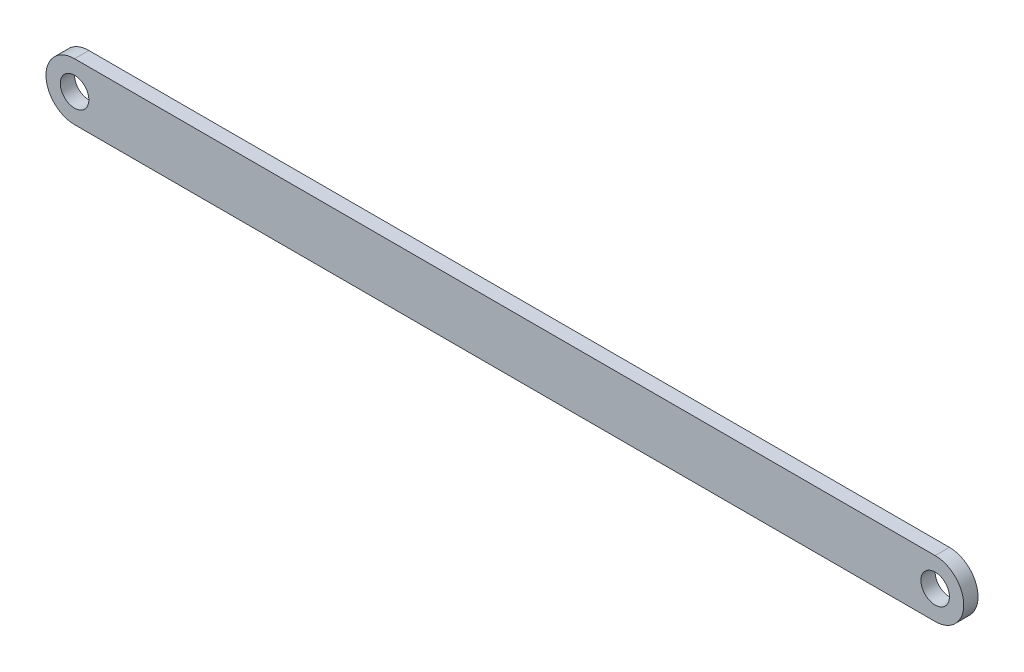
SolidWorks part; units mm, degrees
ref_plane "Plano frontal" through (0, 0, 0) normal (0, 0, 1) x (1, 0, 0)
ref_plane "Plano superior" through (0, 0, 0) normal (0, 1, 0) x (1, 0, 0)
ref_plane "Plano direito" through (0, 0, 0) normal (1, 0, 0) x (0, 0, -1)
sketch "Esboço1" plane through (0, 0, 0) normal (0, 0, 1) x (1, 0, 0)
  line L0 (-30.13, 2) -> (30.13, 2)
  line L1 (-30.13, 0) -> (30.13, 0) construction
  line L2 (-30.13, -2) -> (30.13, -2)
  arc A0 (-30.13, 2) -> (-30.13, -2) centre (-30.13, 0) ccw
  arc A1 (30.13, 2) -> (30.13, -2) centre (30.13, 0) cw
  circle A2 centre (-30.13, 0) radius 1
  circle A3 centre (30.13, 0) radius 1
  point P3 (0, 2)
  dimension "D1" = 60.26
  dimension "D2" = 2
extrude "Ressalto-extrusão1" add sketch "Esboço1" along normal blind 1
